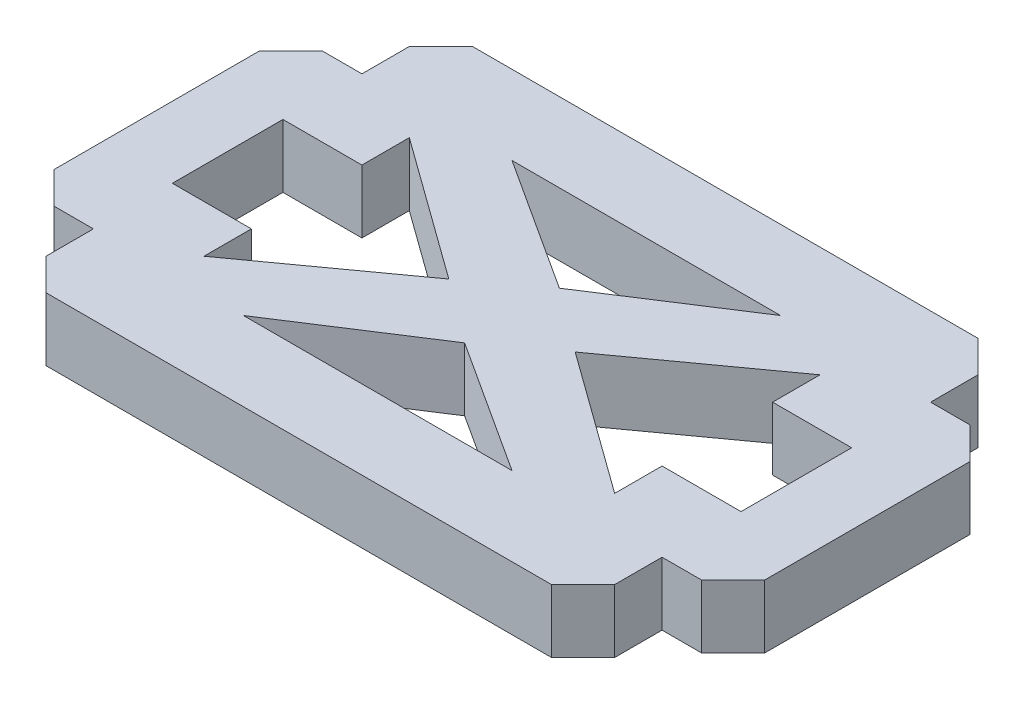
SolidWorks part; units mm, degrees
material "Plain Carbon Steel"
ref_plane "Front Plane" through (0, 0, 0) normal (0, 0, 1) x (1, 0, 0)
ref_plane "Top Plane" through (0, 0, 0) normal (0, 1, 0) x (1, 0, 0)
ref_plane "Right Plane" through (0, 0, 0) normal (1, 0, 0) x (0, 0, -1)
sketch "Sketch2" plane through (0, 0, 0) normal (0, 1, 0) x (1, 0, 0)
  line L0 (18, 8.5) -> (22.5, 8.5)
  line L1 (-22.5, -8.5) -> (-18, -8.5)
  line L2 (-22.5, -8.5) -> (-22.5, 8.5)
  line L3 (-22.5, 8.5) -> (-18, 8.5)
  line L4 (22.5, -8.5) -> (22.5, 8.5)
  line L5 (-22.5, -8.5) -> (22.5, 8.5) construction
  line L6 (-22.5, 8.5) -> (22.5, -8.5) construction
  line L7 (-18, -13.5) -> (18, -13.5)
  line L8 (-18, -13.5) -> (-18, -8.5)
  line L9 (-18, 13.5) -> (18, 13.5)
  line L10 (18, -13.5) -> (18, -8.5)
  line L11 (-18, -13.5) -> (18, 13.5) construction
  line L12 (-18, 13.5) -> (18, -13.5) construction
  line L13 (-18, 8.5) -> (-18, 13.5)
  line L14 (18, -8.5) -> (22.5, -8.5)
  line L15 (18, 8.5) -> (18, 13.5)
  line L16 (0, 0) -> (22.5, 0) construction
  line L17 (0, 17) -> (0, 0) construction
  line L18 (4, 0) -> (13, 6.5)
  line L19 (13, 6.5) -> (13, 3.5)
  line L20 (13, 3.5) -> (18, 3.5)
  line L21 (18, 3.5) -> (18, -3.5)
  line L22 (13, -3.5) -> (18, -3.5)
  line L23 (13, -6.5) -> (13, -3.5)
  line L24 (4, 0) -> (13, -6.5)
  line L25 (-8.5, 8.5) -> (8.5, 8.5)
  line L26 (8.5, 8.5) -> (0, 3)
  line L27 (-8.5, 8.5) -> (0, 3)
  line L28 (-13, 6.5) -> (-13, 3.5)
  line L29 (-13, 3.5) -> (-18, 3.5)
  line L30 (-18, 3.5) -> (-18, -3.5)
  line L31 (-13, -3.5) -> (-18, -3.5)
  line L32 (-13, -6.5) -> (-13, -3.5)
  line L33 (-4, 0) -> (-13, -6.5)
  line L34 (-4, 0) -> (-13, 6.5)
  line L35 (8.5, 8.5) -> (0, 3)
  line L36 (-8.5, 8.5) -> (0, 3)
  line L37 (0, -17) -> (0, 0) construction
  line L38 (-18, 13.5) -> (18, -13.5) construction
  line L39 (-8.5, -8.5) -> (0, -3)
  line L40 (8.5, -8.5) -> (0, -3)
  line L41 (-8.5, -8.5) -> (0, -3)
  line L42 (8.5, -8.5) -> (0, -3)
  line L43 (-8.5, -8.5) -> (8.5, -8.5)
  point P0 (0, 0)
  point P6 (0, 0)
  point P24 (18, 0)
  point P30 (0, 8.5)
  point P44 (0, -8.5)
  dimension "D1" = 45
  dimension "D2" = 36
  dimension "D3" = 17
  dimension "D4" = 3
  dimension "D5" = 5
  dimension "D6" = 5
  dimension "D7" = 5
  dimension "D8" = 4
  dimension "D9" = 17
  dimension "D10" = 3
extrude "Boss-Extrude1" add sketch "Sketch2" along normal blind 4 contours L0 L15 L9 L13 L3 L2 L1 L8 L7 L10 L14 L4 L43 L39 L40 L34 L33 L32 L31 L30 L29 L28 L27 L25 L26 L24 L18 L19 L20 L21 L22 L23
chamfer "Chamfer1" distance 2 angle 45 8 edges at (-22.5, 2, -8.5) (-18, 2, -13.5) (18, 2, -13.5) (22.5, 2, -8.5) (22.5, 2, 8.5) (18, 2, 13.5) (-18, 2, 13.5) (-22.5, 2, 8.5)
